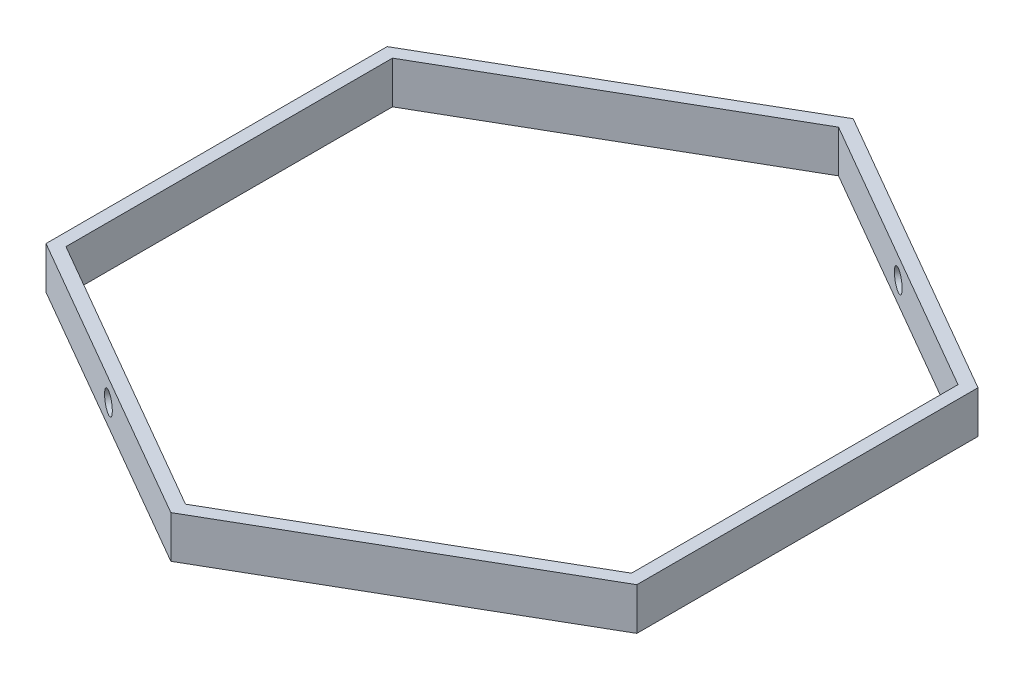
SolidWorks part; units mm, degrees
ref_plane "Plano frontal" through (0, 0, 0) normal (0, 0, 1) x (1, 0, 0)
ref_plane "Plano superior" through (0, 0, 0) normal (0, 1, 0) x (1, 0, 0)
ref_plane "Plano direito" through (0, 0, 0) normal (1, 0, 0) x (0, 0, -1)
sketch "Esboço1" plane through (0, 0, 0) normal (0, 1, 0) x (1, 0, 0)
  line L0 (28, -16.1658) -> (28, 16.1658)
  line L1 (28, 16.1658) -> (0, 32.3316)
  line L2 (0, 32.3316) -> (-28, 16.1658)
  line L3 (-28, 16.1658) -> (-28, -16.1658)
  line L4 (-28, -16.1658) -> (0, -32.3316)
  line L5 (0, -32.3316) -> (28, -16.1658)
  line L6 (26.8, 15.473) -> (0, 30.946)
  line L7 (0, 30.946) -> (-26.8, 15.473)
  line L8 (-26.8, 15.473) -> (-26.8, -15.473)
  line L9 (-26.8, -15.473) -> (0, -30.946)
  line L10 (0, -30.946) -> (26.8, -15.473)
  line L11 (26.8, -15.473) -> (26.8, 15.473)
  circle A0 centre (0, 0) radius 28 construction
  point P1 (0, 0)
  dimension "D1" = 56
  dimension "D2" = 1.2
extrude "Ressalto-extrusão1" add sketch "Esboço1" along normal blind 4
sketch "Esboço2" plane through (-14, 0, 24.2487) normal (-0.5, 0, 0.866) x (0.866, 0, 0.5)
  line L0 (-16.1658, 2) -> (0, 2) construction
  line L1 (-16.1658, 4) -> (-16.1658, 0) construction
  line L2 (0, 2) -> (16.1658, 2) construction
  line L3 (16.1658, 4) -> (16.1658, 0) construction
  circle A0 centre (0, 2) radius 1
  dimension "D1" = 2
extrude "Corte-extrusão1" cut sketch "Esboço2" against normal through all
